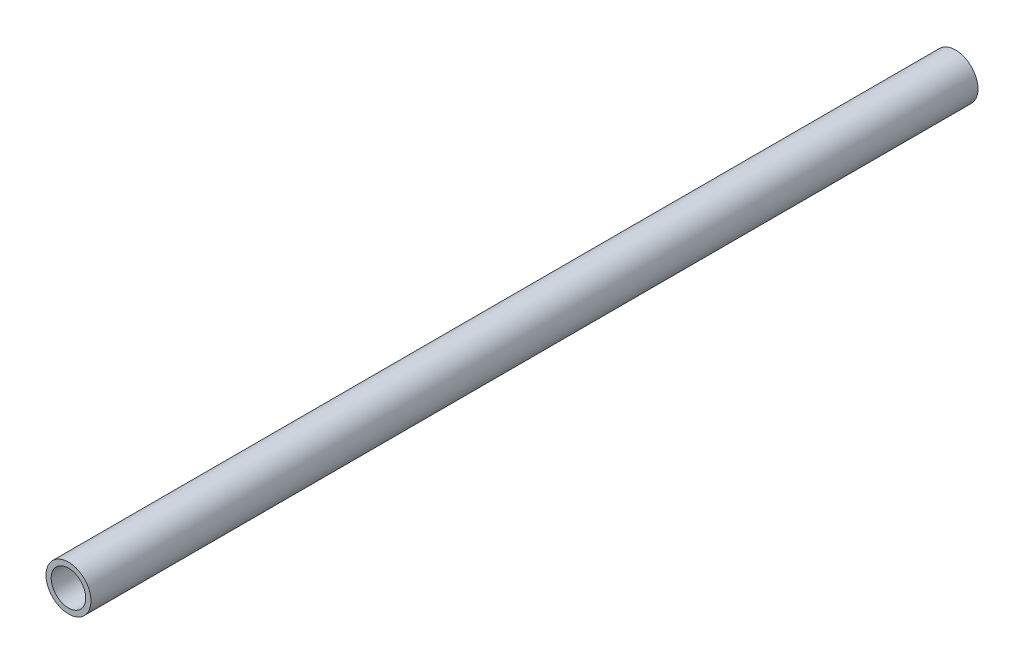
SolidWorks part; units mm, degrees
material "AISI 4130 Steel, annealed at 865C"
ref_plane "X-Y Datum" through (0, 0, 0) normal (0, 0, 1) x (1, 0, 0)
ref_plane "X-Z Datum" through (0, 0, 0) normal (0, 1, 0) x (1, 0, 0)
ref_plane "Y-Z Datum" through (0, 0, 0) normal (1, 0, 0) x (0, 0, -1)
sketch "Sketch1" plane through (0, 0, 0) normal (0, 0, 1) x (1, 0, 0)
  circle A0 centre (0, 0) radius 4.8768
  circle A1 centre (0, 0) radius 6.35
  dimension "D1" = 12.7
  dimension "D2" = 1.4732
extrude "Boss-Extrude1" add sketch "Sketch1" along normal up to surface (250.4897 mm away)
